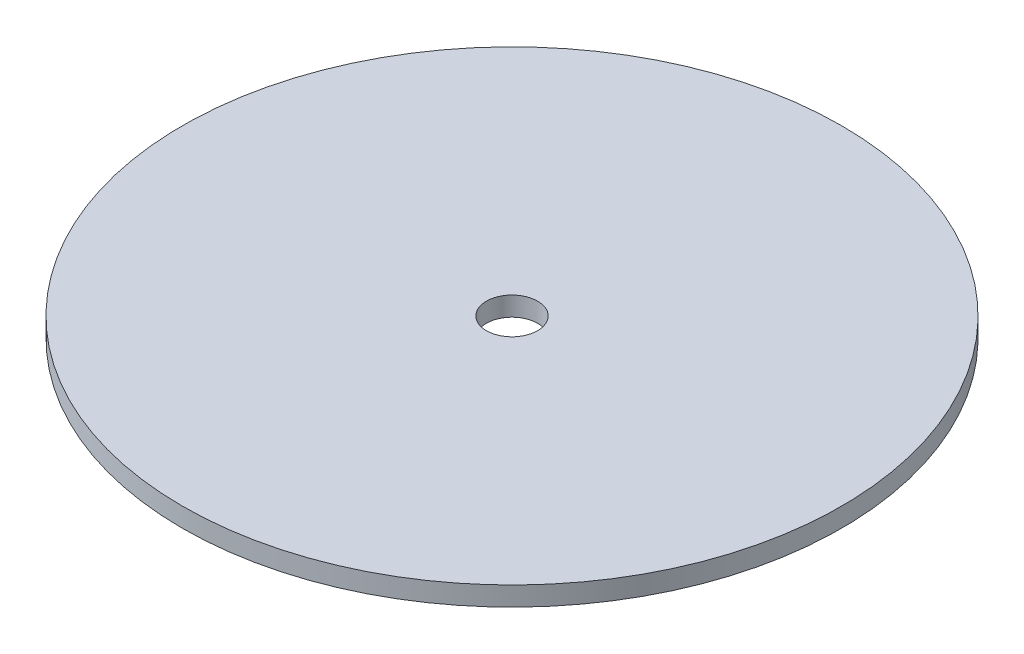
SolidWorks part; units mm, degrees
ref_plane "Front Plane" through (0, 0, 0) normal (0, 0, 1) x (1, 0, 0)
ref_plane "Top Plane" through (0, 0, 0) normal (0, 1, 0) x (1, 0, 0)
ref_plane "Right Plane" through (0, 0, 0) normal (1, 0, 0) x (0, 0, -1)
sketch "Sketch1" plane through (0, 0, 0) normal (0, 1, 0) x (1, 0, 0)
  circle A0 centre (0, 0) radius 10.3
  circle A1 centre (0, 0) radius 0.8
extrude "Extrude1" add sketch "Sketch1" along normal blind 0.6
